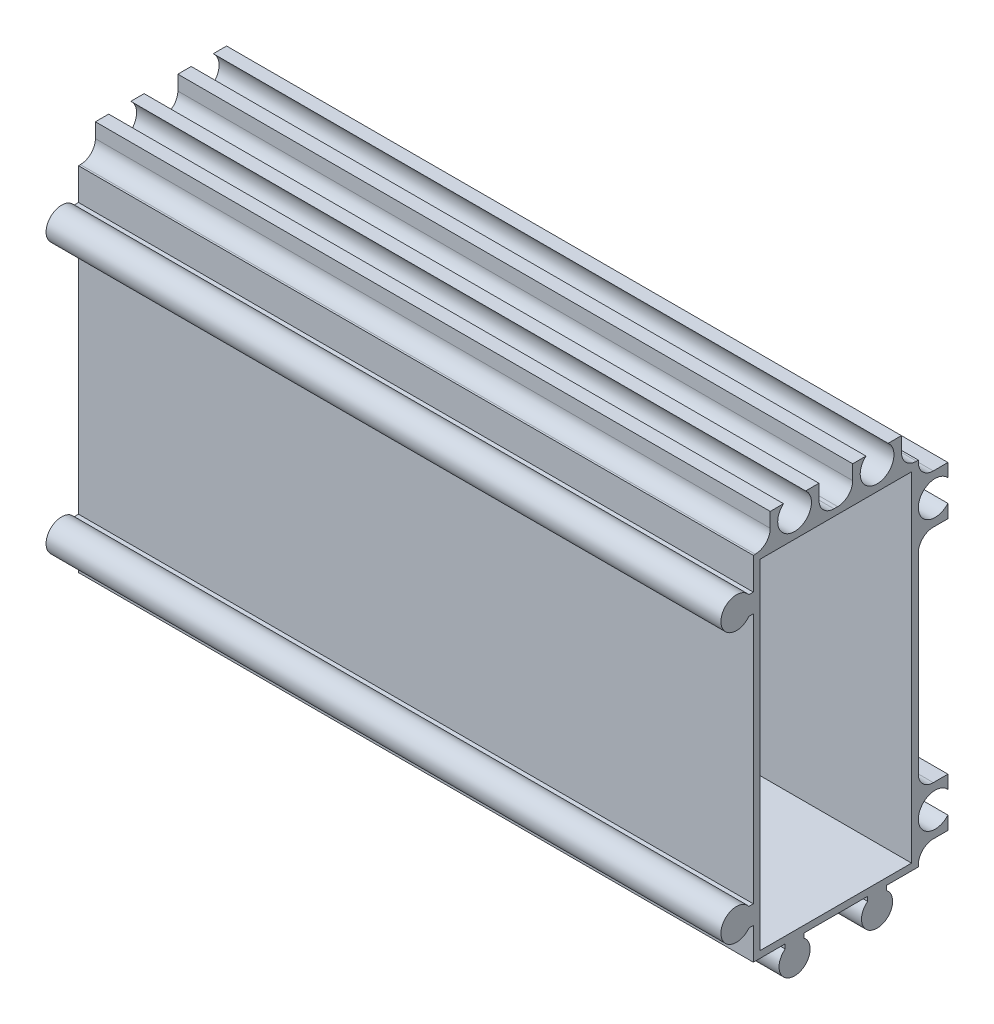
SolidWorks part; units mm, degrees
ref_plane "Спереди" through (0, 0, 0) normal (0, 0, 1) x (1, 0, 0)
ref_plane "Сверху" through (0, 0, 0) normal (0, 1, 0) x (1, 0, 0)
ref_plane "Справа" through (0, 0, 0) normal (1, 0, 0) x (0, 0, -1)
ref_plane "Плоскость4" through (90, 0, 0) normal (1, 0, 0) x (0, 0, -1)
sketch "Эскиз1" plane through (90, 0, 0) normal (1, 0, 0) x (0, 0, -1)
  line L0 (6.75, -24.0938) -> (6.75, 19.25)
  line L1 (6.75, 19.25) -> (-11.5938, 19.25)
  line L2 (-11.5938, 16.75) -> (-11, 16.75)
  line L3 (-11, 16.75) -> (-11, -16.75)
  line L4 (-11, -16.75) -> (-11.5938, -16.75)
  line L5 (-11.5938, -19.25) -> (-11, -19.25)
  line L6 (-11, -19.25) -> (-11, -23.5)
  line L7 (-11, -23.5) -> (-6.75, -23.5)
  line L8 (-6.75, -23.5) -> (-6.75, -24.0938)
  line L9 (-4.25, -24.0938) -> (-4.25, -23.5)
  line L10 (-4.25, -23.5) -> (4.25, -23.5)
  line L11 (4.25, -23.5) -> (4.25, -24.0938)
  arc A0 (-11.5938, 19.25) -> (-11.5938, 16.75) centre (-13.25, 18) ccw
  arc A1 (-11.5938, -16.75) -> (-11.5938, -19.25) centre (-13.25, -18) ccw
  arc A2 (-6.75, -24.0938) -> (-4.25, -24.0938) centre (-5.5, -25.75) ccw
  arc A3 (4.25, -24.0938) -> (6.75, -24.0938) centre (5.5, -25.75) ccw
extrude "Бобышка-Вытянуть1" add sketch "Эскиз1" against normal blind 90
sketch "Эскиз2" plane through (0, 19.25, 0) normal (0, 1, 0) x (-1, 0, 0)
  line L0 (-90, -6.75) -> (-90, 11)
  line L1 (-90, 11) -> (0, 11)
  line L2 (0, 11) -> (0, -6.75)
  line L3 (0, -6.75) -> (-90, -6.75)
extrude "Бобышка-Вытянуть2" add sketch "Эскиз2" along normal blind 8.2
sketch "Эскиз3" plane through (0, 0, -6.75) normal (0, 0, -1) x (-1, 0, 0)
  line L0 (0, -23.5) -> (-90, -23.5)
  line L1 (-90, -23.5) -> (-90, 27.45)
  line L2 (-90, 27.45) -> (0, 27.45)
  line L3 (0, 27.45) -> (0, -23.5)
extrude "Бобышка-Вытянуть3" add sketch "Эскиз3" along normal blind 8.2
sketch "Эскиз4" plane through (0, 0, 0) normal (-1, 0, 0) x (0, 0, 1)
  line L0 (-14.95, -14.75) -> (-11, -14.75)
  line L1 (-11, -14.75) -> (-11, 14.75)
  line L2 (-11, 14.75) -> (-14.95, 14.75)
  line L3 (-14.95, 14.75) -> (-14.95, -14.75)
extrude "Вырез-Вытянуть1" cut sketch "Эскиз4" against normal through all
sketch "Эскиз5" plane through (0, 0, 0) normal (-1, 0, 0) x (0, 0, 1)
  line L0 (-14.95, 27.45) -> (-14.95, 21.25)
  line L1 (-14.95, 21.25) -> (-11, 21.25)
  line L2 (-11, 21.25) -> (-11, 27.45)
  line L3 (-11, 27.45) -> (-14.95, 27.45)
extrude "Вырез-Вытянуть2" cut sketch "Эскиз5" against normal through all
sketch "Эскиз6" plane through (0, 0, 0) normal (-1, 0, 0) x (0, 0, 1)
  line L0 (-11, 27.45) -> (-11, 23.5)
  line L1 (-11, 23.5) -> (-8.75, 23.5)
  line L2 (-8.75, 23.5) -> (-8.75, 27.45)
  line L3 (-8.75, 27.45) -> (-11, 27.45)
extrude "Вырез-Вытянуть3" cut sketch "Эскиз6" against normal through all
sketch "Эскиз7" plane through (0, 0, 0) normal (-1, 0, 0) x (0, 0, 1)
  line L0 (-2.25, 27.45) -> (-2.25, 23.5)
  line L1 (-2.25, 23.5) -> (2.25, 23.5)
  line L2 (2.25, 23.5) -> (2.25, 27.45)
  line L3 (2.25, 27.45) -> (-2.25, 27.45)
extrude "Вырез-Вытянуть4" cut sketch "Эскиз7" against normal through all
sketch "Эскиз8" plane through (0, 0, 0) normal (-1, 0, 0) x (0, 0, 1)
  line L0 (11, 27.45) -> (8.75, 27.45)
  line L1 (8.75, 27.45) -> (8.75, 23.5)
  line L2 (8.75, 23.5) -> (11, 23.5)
  line L3 (11, 23.5) -> (11, 27.45)
extrude "Вырез-Вытянуть5" cut sketch "Эскиз8" against normal through all
sketch "Эскиз9" plane through (0, 0, 0) normal (-1, 0, 0) x (0, 0, 1)
  line L0 (-14.95, -23.5) -> (-11, -23.5)
  line L1 (-11, -23.5) -> (-11, -21.25)
  line L2 (-11, -21.25) -> (-14.95, -21.25)
  line L3 (-14.95, -21.25) -> (-14.95, -23.5)
extrude "Вырез-Вытянуть6" cut sketch "Эскиз9" against normal through all
sketch "Эскиз10" plane through (90, 0, 0) normal (1, 0, 0) x (0, 0, -1)
  line L0 (10.1, 22.6) -> (-10.1, 22.6)
  line L1 (-10.1, 22.6) -> (-10.1, -22.6)
  line L2 (-10.1, -22.6) -> (10.1, -22.6)
  line L3 (10.1, -22.6) -> (10.1, 22.6)
extrude "Вырез-Вытянуть7" cut sketch "Эскиз10" against normal blind 86
hole_wizard "Диаметр отверстия Ø2.5 (2.5)1" positions "Эскиз12" profile "Эскиз11" hole size "Ø2.5" standard "Ansi Metric"
sketch "Эскиз12" plane through (90, 0, 0) normal (1, 0, 0) x (0, 0, -1)
  point P0 (5.5, -25.75)
  point P1 (-13.25, -18)
  point P2 (-5.5, -25.75)
  point P3 (-13.25, 18)
sketch "Эскиз11" plane through (90, -25.75, -5.5) normal (0, 1, 0) x (0, 0, -1)
  line L0 (0, 0) -> (0, 90)
  line L1 (0, 90) -> (1.25, 90)
  line L2 (1.25, 90) -> (1.25, 0)
  line L5 (1.25, 0) -> (0, 0)
  line L11 (0, -6.35) -> (0, 107.95) construction
  dimension "Диаметр сквозного отверстия" = 2.5
  dimension "Глубина сквозного отверстия" = 90
hole_wizard "Диаметр отверстия Ø4.5 (4.5)1" positions "Эскиз14" profile "Эскиз13" hole size "Ø4.5" standard "Ansi Metric"
sketch "Эскиз14" plane through (0, 0, 0) normal (-1, 0, 0) x (0, 0, 1)
  point P0 (-13.25, -18)
  point P1 (-13.25, 18)
  point P2 (-5.5, 25.75)
  point P3 (5.5, 25.75)
sketch "Эскиз13" plane through (0, -18, -13.25) normal (0, 1, 0) x (0, 0, 1)
  line L0 (0, 0) -> (0, 90)
  line L1 (0, 90) -> (2.25, 90)
  line L2 (2.25, 90) -> (2.25, 0)
  line L5 (2.25, 0) -> (0, 0)
  line L11 (0, -6.35) -> (0, 107.95) construction
  dimension "Диаметр сквозного отверстия" = 4.5
  dimension "Глубина сквозного отверстия" = 90
hole_wizard "Диаметр отверстия Ø8.3 (8.3)1" positions "Эскиз16" profile "Эскиз15" hole size "Ø8.3" standard "Ansi Metric"
sketch "Эскиз16" plane through (0, 0, 0) normal (-1, 0, 0) x (0, 0, 1)
  point P0 (0, 0)
sketch "Эскиз15" plane through (0, 0, 0) normal (0, 1, 0) x (0, 0, 1)
  line L0 (0, 0) -> (0, 3.2)
  line L1 (0, 3.2) -> (4.15, 3.2)
  line L2 (4.15, 3.2) -> (4.15, 0)
  line L5 (4.15, 0) -> (0, 0)
  line L10 (0, 3.2) -> (-4.15, 3.2) construction
  line L11 (0, -6.35) -> (0, 107.95) construction
  dimension "Диаметр отверстия" = 8.3
  dimension "Глубина отверстия" = 3.2
  dimension "Угол заточки сверла" = 180
fillet "Скругление1" radius 2 1 edges at (45, 23.5, 8.75)
fillet "Скругление2" radius 2 11 edges at (4, -22.6, 0) (4, 0, -10.1) (4, 0, 10.1) (4, 22.6, 0) (45, -21.25, -11) (45, -14.75, -11) (45, 14.75, -11) (45, 21.25, -11) (45, 23.5, -8.75) (45, 23.5, -2.25) (45, 23.5, 2.25)
sketch "Эскиз17" plane through (90, 0, 0) normal (1, 0, 0) x (0, 0, -1)
  circle A0 centre (5.5, -25.75) radius 1.25 construction
  circle A1 centre (-5.5, -25.75) radius 1.25 construction
  circle A2 centre (-13.25, -18) radius 1.25 construction
  circle A3 centre (-13.25, 18) radius 1.25 construction
  circle A4 centre (5.5, -25.75) radius 1.25
  circle A5 centre (-5.5, -25.75) radius 1.25
  circle A6 centre (-13.25, -18) radius 1.25
  circle A7 centre (-13.25, 18) radius 1.25
extrude "Бобышка-Вытянуть4" add sketch "Эскиз17" against normal blind 90
sketch "Эскиз18" plane through (0, 0, 0) normal (-1, 0, 0) x (0, 0, 1)
  circle A0 centre (0, 0) radius 4.15 construction
  circle A1 centre (0, 0) radius 4.15
extrude "Вырез-Вытянуть8" cut sketch "Эскиз18" against normal blind 100
